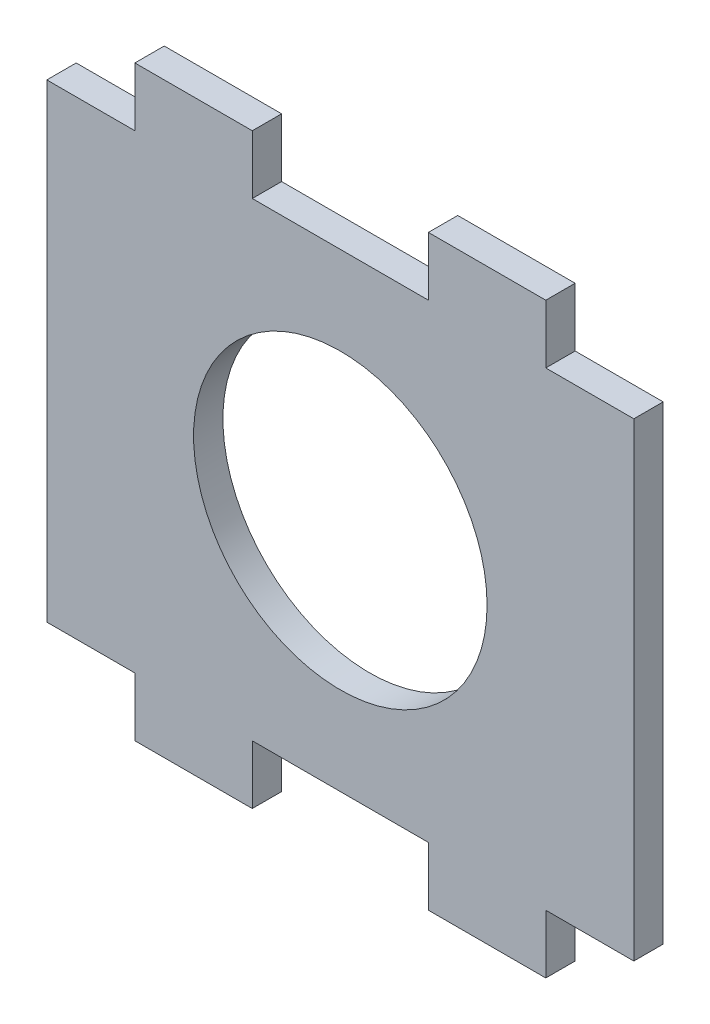
SolidWorks part; units mm, degrees
ref_plane "Front Plane" through (0, 0, 0) normal (0, 0, 1) x (1, 0, 0)
ref_plane "Top Plane" through (0, 0, 0) normal (0, 1, 0) x (1, 0, 0)
ref_plane "Right Plane" through (0, 0, 0) normal (1, 0, 0) x (0, 0, -1)
sketch "Sketch1" plane through (0, 0, 0) normal (0, 0, 1) x (1, 0, 0)
  line L1 (31.75, -25.4) -> (-31.75, -25.4)
  line L2 (31.75, -25.4) -> (31.75, 25.4)
  line L3 (31.75, 25.4) -> (-31.75, 25.4)
  line L4 (-31.75, -25.4) -> (-31.75, 25.4)
  line L5 (31.75, -25.4) -> (-31.75, 25.4) construction
  line L6 (31.75, 25.4) -> (-31.75, -25.4) construction
  line L7 (-22.225, 25.4) -> (-9.525, 25.4)
  line L8 (-22.225, 25.4) -> (-22.225, 31.75)
  line L9 (-22.225, 31.75) -> (-9.525, 31.75)
  line L10 (-9.525, 25.4) -> (-9.525, 31.75)
  line L11 (9.525, 25.4) -> (22.225, 25.4)
  line L12 (9.525, 25.4) -> (9.525, 31.75)
  line L13 (9.525, 31.75) -> (22.225, 31.75)
  line L14 (22.225, 25.4) -> (22.225, 31.75)
  line L15 (-22.225, -25.4) -> (-9.525, -25.4)
  line L16 (-22.225, -25.4) -> (-22.225, -31.75)
  line L17 (-22.225, -31.75) -> (-9.525, -31.75)
  line L18 (-9.525, -25.4) -> (-9.525, -31.75)
  line L19 (9.525, -25.4) -> (22.225, -25.4)
  line L20 (9.525, -25.4) -> (9.525, -31.75)
  line L21 (9.525, -31.75) -> (22.225, -31.75)
  line L22 (22.225, -25.4) -> (22.225, -31.75)
  circle A0 centre (0, 0) radius 15.875
  point P0 (0, 0)
  dimension "D3" = 31.75
  dimension "D1" = 63.5
  dimension "D2" = 50.8
  dimension "D4" = 6.35
  dimension "D5" = 6.35
  dimension "D6" = 12.7
  dimension "D7" = 12.7
  dimension "D8" = 9.525
  dimension "D9" = 9.525
  dimension "D10" = 6.35
  dimension "D11" = 6.35
  dimension "D12" = 12.7
  dimension "D13" = 12.7
  dimension "D14" = 9.525
  dimension "D15" = 9.525
extrude "Boss-Extrude1" add sketch "Sketch1" along normal blind 3.175 contours L3 L10 L9 L8 | L4 L1 L2 L3 A0 | L3 L14 L13 L12 | L22 L1 L20 L21 | L18 L1 L16 L17
